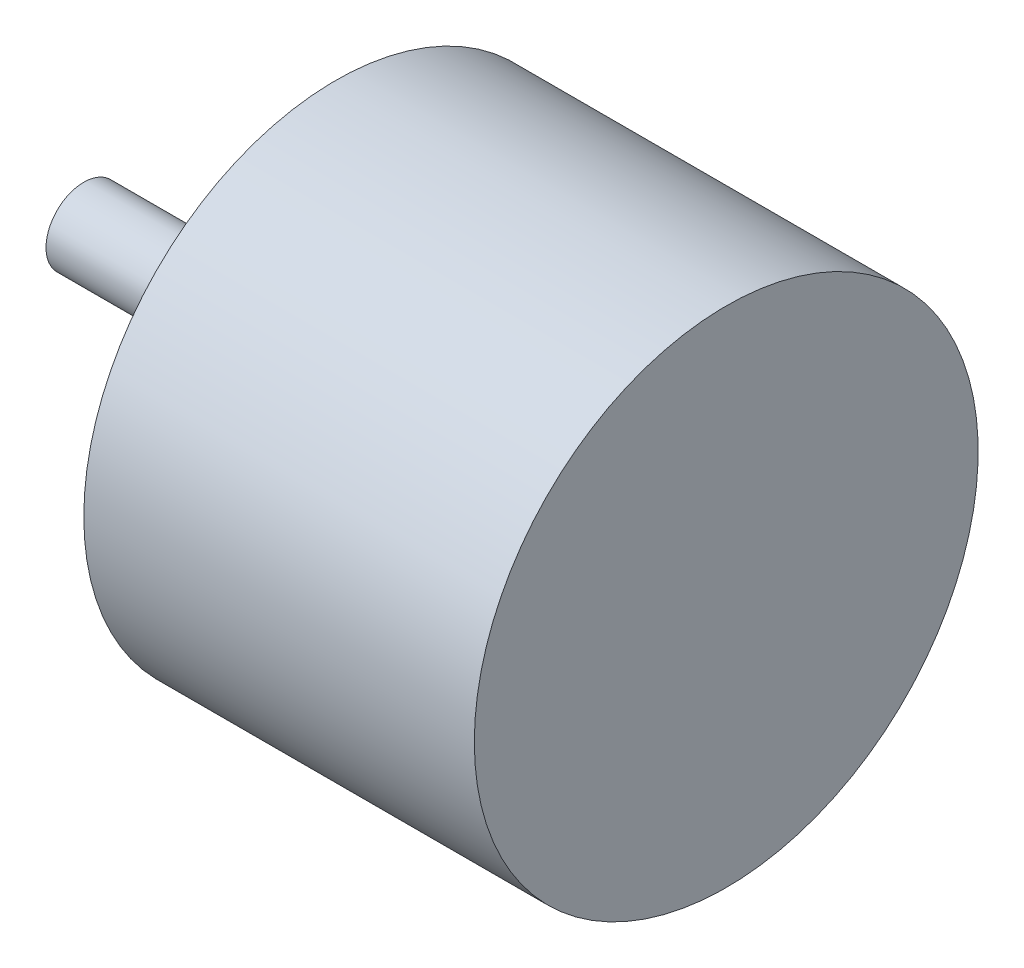
SolidWorks part; units mm, degrees
ref_plane "Front Plane" through (0, 0, 0) normal (0, 0, 1) x (1, 0, 0)
ref_plane "Top Plane" through (0, 0, 0) normal (0, 1, 0) x (1, 0, 0)
ref_plane "Right Plane" through (0, 0, 0) normal (1, 0, 0) x (0, 0, -1)
sketch "Sketch1" plane through (0, 0, 0) normal (0, 0, 1) x (1, 0, 0)
  line L0 (-28.1538, 0) -> (29.6538, 0) construction
  line L1 (-24.5, 0) -> (-24.5, 3)
  line L2 (-24.5, 3) -> (-9.5, 3)
  line L3 (-9.5, 3) -> (-9.5, 10)
  line L4 (-9.5, 10) -> (-4.5, 10)
  line L5 (-4.5, 10) -> (-4.5, 20)
  line L6 (-4.5, 20) -> (26.5, 20)
  line L7 (26.5, 20) -> (26.5, 0)
  line L8 (-24.5, 0) -> (26.5, 0)
  dimension "D1" = 3
  dimension "D2" = 15
  dimension "D3" = 5
  dimension "D4" = 31
  dimension "D5" = 7
  dimension "D6" = 20
  dimension "D7" = 26.5
revolve "Revolve1" add sketch "Sketch1" angle 360 about L0
sketch "Sketch2" plane through (-4.5, 0, 0) normal (-1, 0, 0) x (0, 0, 1)
  circle A9 centre (15, 0) radius 1.5
  circle A11 centre (0, 0) radius 15 construction
  circle A12 centre (-7.5, -12.9904) radius 1.5
  circle A13 centre (-7.5, 12.9904) radius 1.5
  point P12 (0, 0)
  dimension "D1" = 3
  dimension "D2" = 30
extrude "Cut-Extrude1" cut sketch "Sketch2" against normal blind 10
